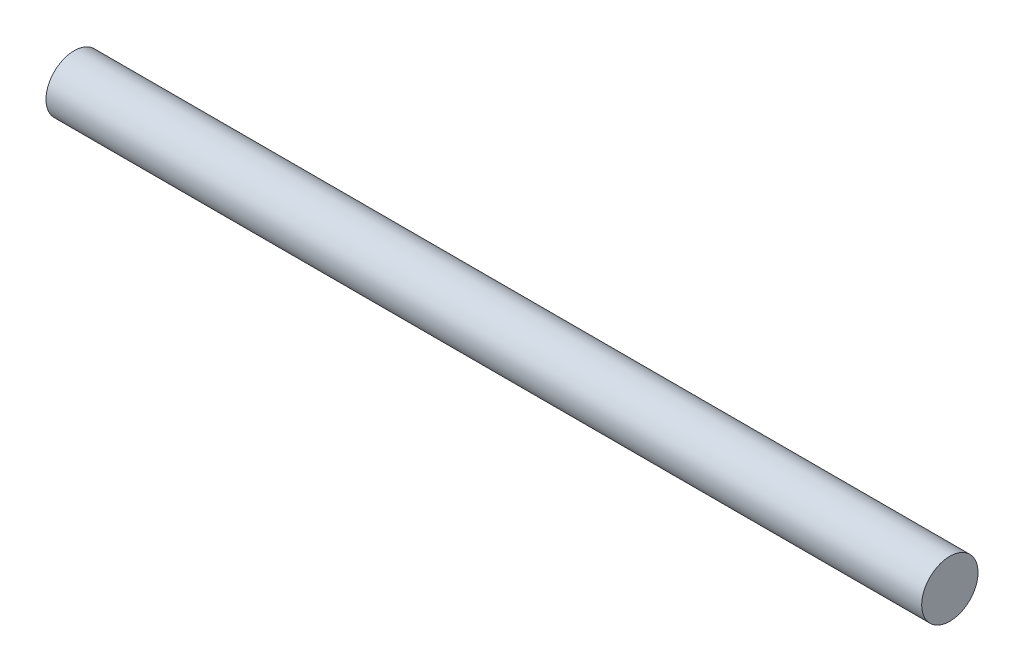
SolidWorks part; units mm, degrees
ref_plane "前视基准面" through (0, 0, 0) normal (0, 0, 1) x (1, 0, 0)
ref_plane "上视基准面" through (0, 0, 0) normal (0, 1, 0) x (1, 0, 0)
ref_plane "右视基准面" through (0, 0, 0) normal (1, 0, 0) x (0, 0, -1)
sketch "草图1" plane through (0, 0, 0) normal (0, 1, 0) x (1, 0, 0)
  line L0 (-70.4918, 0) -> (118.2598, 0) construction
  line L1 (0, -75.4557) -> (0, 43.0627) construction
  line L2 (0, 0) -> (0, -8.5)
  line L3 (0, -8.5) -> (264, -8.5)
  line L4 (264, -8.5) -> (264, 0)
  line L5 (0, 0) -> (264, 0)
revolve "旋转1" add sketch "草图1" angle 360 about L0
